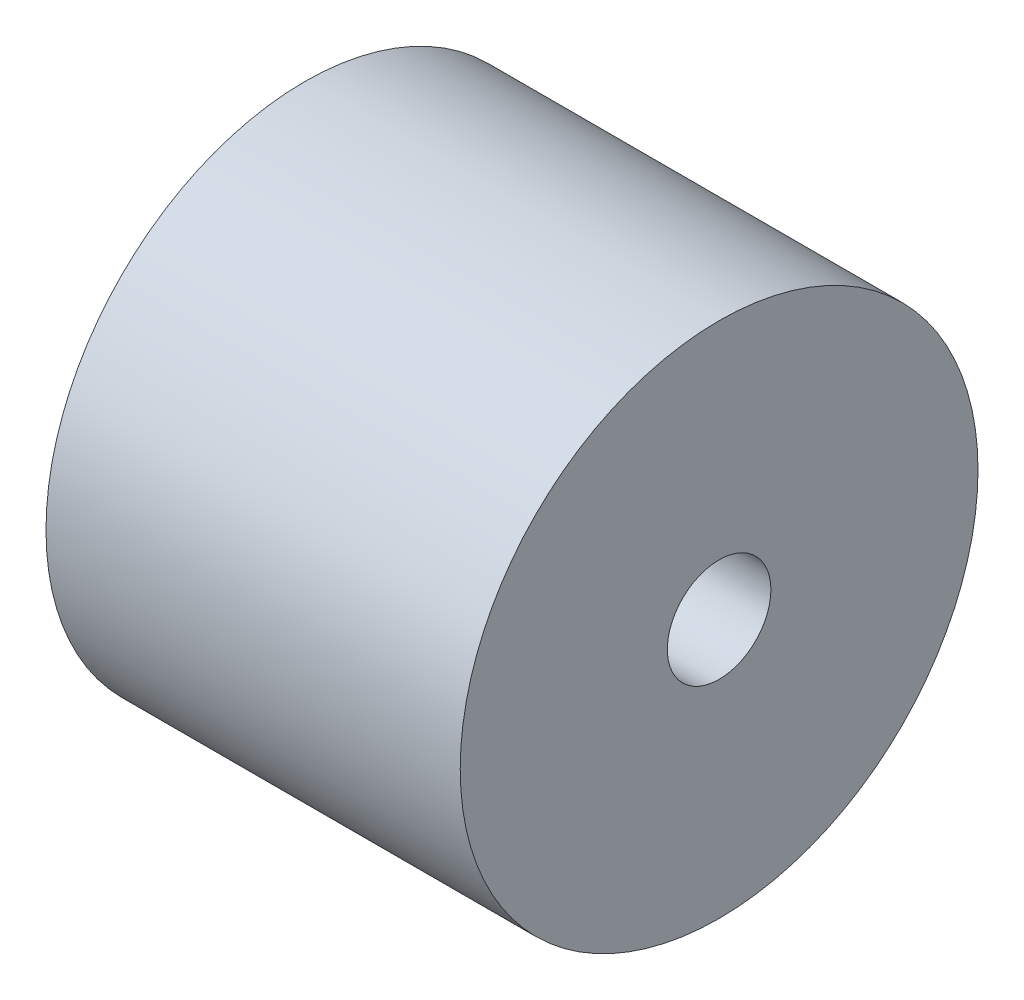
SolidWorks part; units mm, degrees
ref_plane "前视基准面" through (0, 0, 0) normal (0, 0, 1) x (1, 0, 0)
ref_plane "上视基准面" through (0, 0, 0) normal (0, 1, 0) x (1, 0, 0)
ref_plane "右视基准面" through (0, 0, 0) normal (1, 0, 0) x (0, 0, -1)
other "Configuration Table"
sketch "草图1" plane through (0, 0, 0) normal (1, 0, 0) x (0, 0, -1)
  circle A0 centre (0, 0) radius 10
  dimension "D1" = 20
extrude "凸台-拉伸1" add sketch "草图1" along normal blind 16
sketch "草图2" plane through (16, 0, 0) normal (1, 0, 0) x (0, 0, -1)
  circle A0 centre (0, 0) radius 2
  dimension "D1" = 4
extrude "切除-拉伸1" cut sketch "草图2" against normal blind 10
cosmetic thread "装饰螺纹线1" parameters "D2"=5
sketch "草图4" plane through (0, 0, 0) normal (-1, 0, 0) x (0, 0, 1)
  circle A0 centre (0, 0) radius 8.4
  dimension "D1" = 16.8
extrude "切除-拉伸2" cut sketch "草图4" against normal blind 1
sketch "草图5" plane through (1, 0, 0) normal (-1, 0, 0) x (0, 0, 1)
  circle A0 centre (0, 0) radius 3.93
  dimension "D1" = 7.86
extrude "凸台-拉伸2" add sketch "草图5" along normal blind 1
